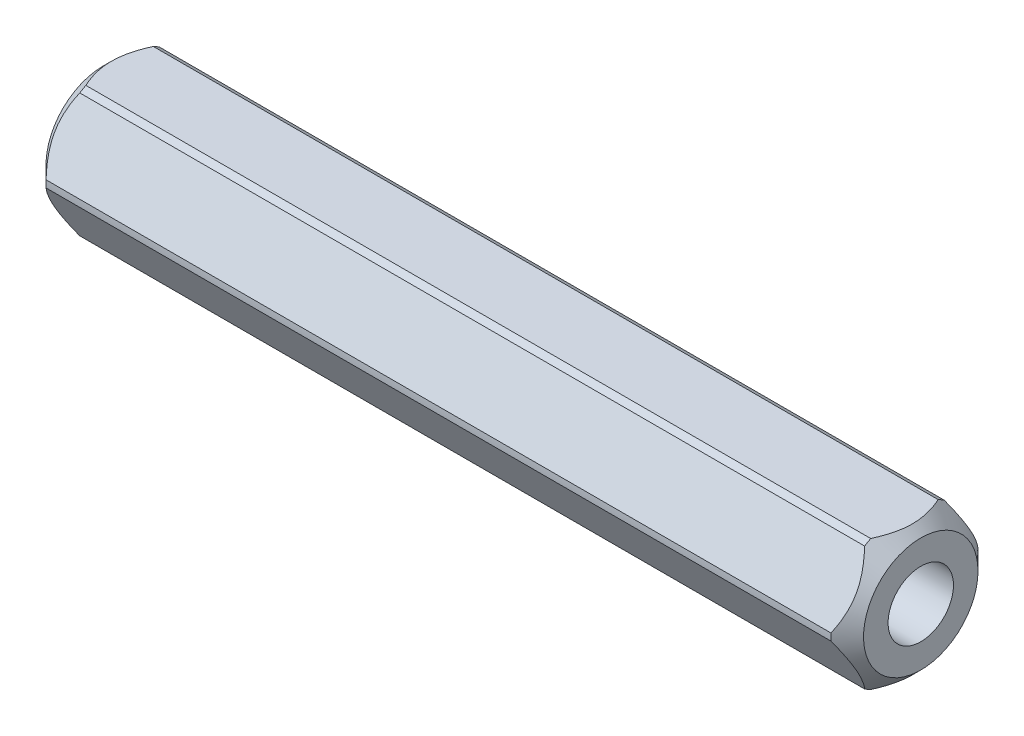
SolidWorks part; units mm, degrees
material "AISI 1045 钢，冷拔"
ref_plane "前视基准面" through (0, 0, 0) normal (0, 0, 1) x (1, 0, 0)
ref_plane "上视基准面" through (0, 0, 0) normal (0, 1, 0) x (1, 0, 0)
ref_plane "右视基准面" through (0, 0, 0) normal (1, 0, 0) x (0, 0, -1)
sketch "草图1" plane through (0, 0, 0) normal (1, 0, 0) x (0, 0, -1)
  line L1 (4.6188, 0) -> (2.3094, 4)
  line L2 (2.3094, 4) -> (-2.3094, 4)
  line L3 (-2.3094, 4) -> (-4.6188, 0)
  line L4 (-4.6188, 0) -> (-2.3094, -4)
  line L5 (-2.3094, -4) -> (2.3094, -4)
  line L6 (2.3094, -4) -> (4.6188, 0)
  circle A1 centre (0, 0) radius 4 construction
  dimension "D1" = 8
extrude "初始整轴" add sketch "草图1" along normal mid plane 50
sketch "草图8" plane through (0, 0, 0) normal (1, 0, 0) x (0, 0, -1)
  circle A0 centre (0, 0) radius 4.5
  circle A1 centre (0, 0) radius 5.5
  dimension "D1" = 9
  dimension "D2" = 1
extrude "整轴外圆" cut sketch "草图8" against normal through all both and the other way through all
sketch "草图9" plane through (0, 0, 0) normal (1, 0, 0) x (0, 0, -1)
  circle A0 centre (0, 0) radius 2
  dimension "D1" = 4
extrude "中心孔切除" cut sketch "草图9" against normal through all both and the other way through all
sketch "草图10" plane through (0, 0, 0) normal (0, 0, 1) x (1, 0, 0)
  line L0 (25, 0) -> (-25, 0) construction
  line L7 (0, 0) -> (0, 3.7854) construction
  line L8 (-25, 3.7854) -> (25, 3.7854) construction
  line L12 (-25.5, 4.5) -> (-24, 4.5)
  line L13 (-25.5, 4.5) -> (-25.5, 3)
  line L14 (-24, 4.5) -> (-25.5, 3)
  line L15 (-25, 3.7854) -> (-25, 0.2146) construction
  line L16 (25, 4) -> (-25, 4) construction
  line L17 (24, 4.5) -> (25.5, 3)
  line L18 (25.5, 4.5) -> (25.5, 3)
  line L19 (25.5, 4.5) -> (24, 4.5)
  line L20 (-25, 0.2146) -> (-25, -0.2146) construction
  point P6 (0, 0)
  point P8 (0, 0)
  dimension "D1" = 1.5
  dimension "D2" = 1.5
  dimension "D3" = 0.5
  dimension "D4" = 0.5
revolve "初始倒角" cut sketch "草图10" angle 360 about L0
sketch "草图2" [suppressed] plane through (25, 0, 0) normal (1, 0, 0) x (0, 0, -1)
  circle A0 centre (0, 0) radius 3.5
  circle A1 centre (0, 0) radius 4.5
  dimension "D1" = 9
  dimension "右侧凸台直径" = 7
extrude "右侧凸台切除" [suppressed] cut sketch "草图2" against normal blind 5
chamfer "右侧凸台倒角" [suppressed] distance 0.3 angle 45
sketch "草图3" [suppressed] plane through (-25, 0, 0) normal (-1, 0, 0) x (0, 0, 1)
  circle A0 centre (0, 0) radius 3.5
  circle A1 centre (0, 0) radius 4.5
  dimension "D1" = 9
  dimension "左侧凸台直径" = 7
extrude "左侧凸台切除" [suppressed] cut sketch "草图3" against normal blind 5
chamfer "左侧凸台倒角" [suppressed] distance 0.3 angle 45
sketch "草图4" plane through (0, 0, 0) normal (0, 0, 1) x (1, 0, 0)
  line L0 (-13.3489, 0) -> (13.3489, 0) construction
  line L3 (14.5, 4.5) -> (15.5, 4.5)
  line L4 (14.5, 4.5) -> (14.5, 3.7)
  line L5 (14.5, 3.7) -> (15.5, 3.7)
  line L6 (15.5, 4.5) -> (15.5, 3.7)
  line L7 (15, 4.5) -> (15, -2.1923) construction
  point P6 (0, 0)
  dimension "D1" = 3.7
  dimension "D2" = 4.5
  dimension "槽1宽度" = 1
  dimension "槽1中心距离" = 15
revolve "卡簧槽1" [suppressed] cut sketch "草图4" angle 360 about L0
sketch "草图5" plane through (0, 0, 0) normal (0, 0, 1) x (1, 0, 0)
  line L0 (-10.9541, 0) -> (10.9541, 0) construction
  line L3 (-15.5, 4.5) -> (-14.5, 4.5)
  line L4 (-15.5, 4.5) -> (-15.5, 3.7)
  line L5 (-15.5, 3.7) -> (-14.5, 3.7)
  line L6 (-14.5, 4.5) -> (-14.5, 3.7)
  line L7 (-15, 4.5) -> (-15, -2.3192) construction
  point P6 (0, 0)
  dimension "D1" = 3.7
  dimension "D2" = 4.5
  dimension "槽2宽度" = 1
  dimension "槽2中心距离" = 15
revolve "卡簧槽2" [suppressed] cut sketch "草图5" angle 360 about L0
sketch "草图6" [suppressed] plane through (25, 0, 0) normal (1, 0, 0) x (0, 0, -1)
  circle A0 centre (0, 0) radius 2.5
  dimension "右侧攻丝直径" = 5
extrude "右侧攻丝切除" [suppressed] cut sketch "草图6" against normal blind 5
chamfer "右侧攻丝倒角" [suppressed] distance 0.5 angle 45
sketch "草图7" [suppressed] plane through (-25, 0, 0) normal (-1, 0, 0) x (0, 0, 1)
  circle A0 centre (0, 0) radius 2.5
  dimension "左侧攻丝直径" = 5
extrude "左侧攻丝切除" [suppressed] cut sketch "草图7" against normal blind 5
chamfer "左侧攻丝倒角" [suppressed] distance 0.5 angle 45
other "冻结***"
